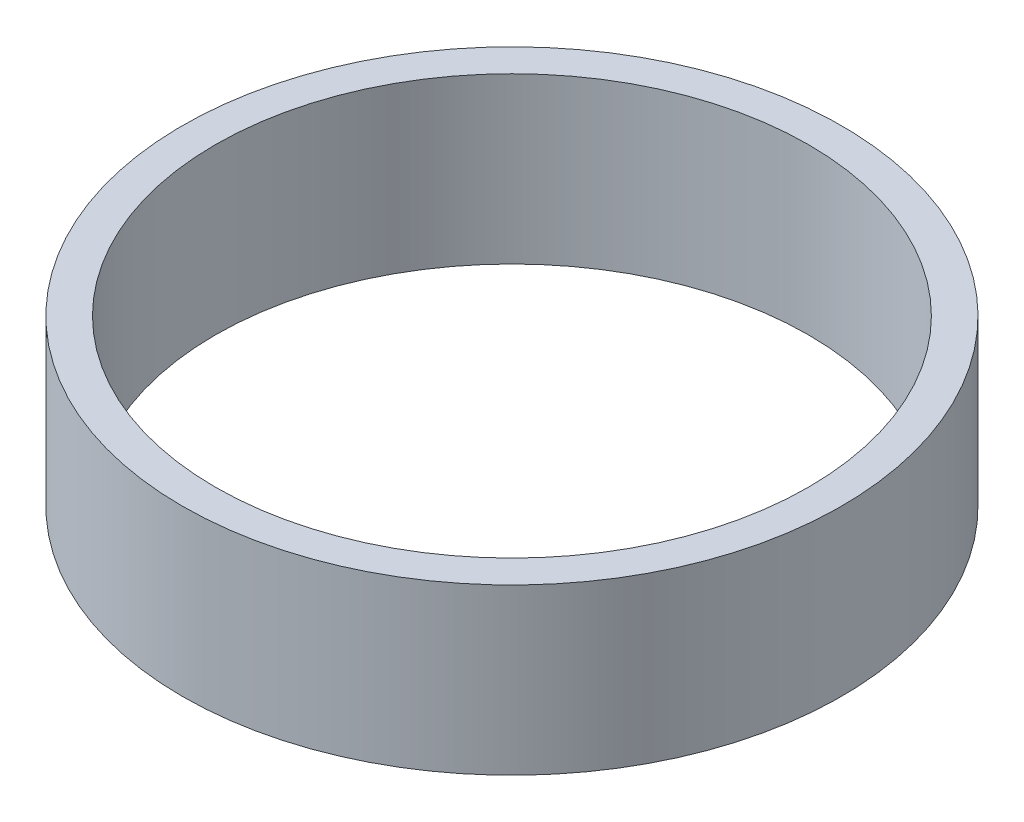
SolidWorks part; units mm, degrees
ref_plane "Front Plane" through (0, 0, 0) normal (0, 0, 1) x (1, 0, 0)
ref_plane "Top Plane" through (0, 0, 0) normal (0, 1, 0) x (1, 0, 0)
ref_plane "Right Plane" through (0, 0, 0) normal (1, 0, 0) x (0, 0, -1)
sketch "Sketch1" plane through (0, 0, 0) normal (0, 1, 0) x (1, 0, 0)
  circle A0 centre (0, 0) radius 36
  circle A1 centre (0, 0) radius 40
  dimension "D1" = 80
  dimension "D2" = 4
extrude "Boss-Extrude1" add sketch "Sketch1" along normal blind 20
